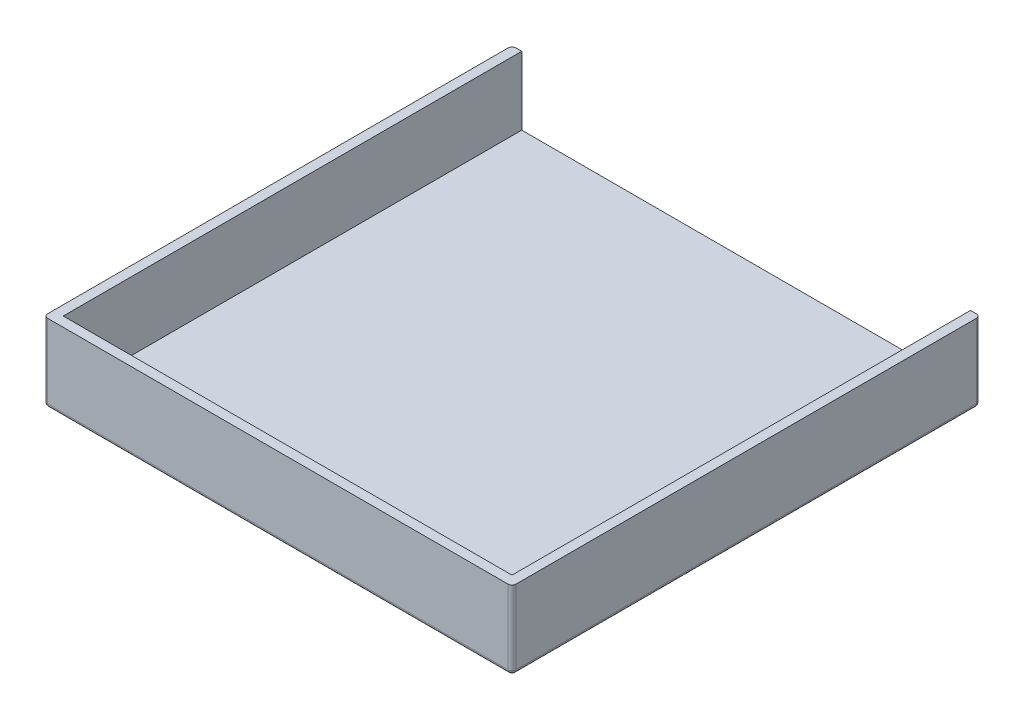
SolidWorks part; units mm, degrees
ref_plane "Front" through (0, 0, 0) normal (0, 0, 1) x (1, 0, 0)
ref_plane "Top" through (0, 0, 0) normal (0, 1, 0) x (1, 0, 0)
ref_plane "Right" through (0, 0, 0) normal (1, 0, 0) x (0, 0, -1)
sketch "Sketch1" plane through (0, 0, 0) normal (0, 1, 0) x (1, 0, 0)
  line L1 (0, 0) -> (304.8, 0)
  line L2 (0, 0) -> (0, 304.8)
  line L3 (0, 304.8) -> (304.8, 304.8)
  line L4 (304.8, 0) -> (304.8, 304.8)
  dimension "D1" = 304.8
  dimension "D2" = 304.8
extrude "Boss-Extrude1" add sketch "Sketch1" along normal blind 50.8
shell "Shell1" thickness 6.35
fillet "Fillet1" radius 2.54 8 edges at (152.4, 0, 0) (304.8, 0, -152.4) (152.4, 0, -304.8) (0, 0, -152.4) (0, 25.4, 0) (304.8, 25.4, 0) (0, 25.4, -304.8) (304.8, 25.4, -304.8)
